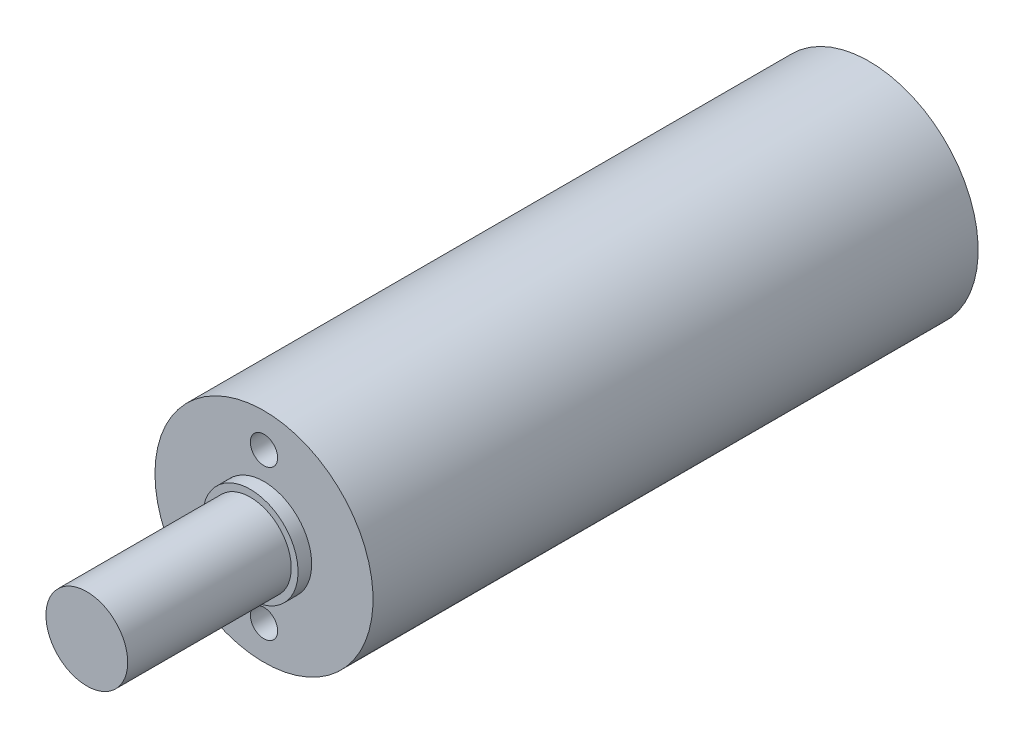
SolidWorks part; units mm, degrees
ref_plane "Front Plane" through (0, 0, 0) normal (0, 0, 1) x (1, 0, 0)
ref_plane "Top Plane" through (0, 0, 0) normal (0, 1, 0) x (1, 0, 0)
ref_plane "Right Plane" through (0, 0, 0) normal (1, 0, 0) x (0, 0, -1)
sketch "Sketch1" plane through (0, 0, 0) normal (0, 0, 1) x (1, 0, 0)
  circle A0 centre (0, 0) radius 3
  dimension "D1" = 6
extrude "Boss-Extrude1" add sketch "Sketch1" along normal blind 12
sketch "Sketch2" plane through (0, 0, 0) normal (0, 0, -1) x (-1, 0, 0)
  circle A0 centre (0, 0) radius 3.5
  dimension "D1" = 7
extrude "Boss-Extrude2" add sketch "Sketch2" along normal blind 1
sketch "Sketch3" plane through (0, 0, -1) normal (0, 0, -1) x (-1, 0, 0)
  circle A0 centre (0, 0) radius 8
  dimension "D1" = 16
extrude "Boss-Extrude3" add sketch "Sketch3" along normal blind 44.4
sketch "Sketch4" plane through (0, 0, -1) normal (0, 0, 1) x (1, 0, 0)
  circle A0 centre (0, 5.5) radius 1
  circle A1 centre (0, -5.5) radius 1
  dimension "D1" = 2
  dimension "D2" = 2
  dimension "D3" = 11
  dimension "D4" = 5.5
extrude "Cut-Extrude1" cut sketch "Sketch4" against normal blind 3
